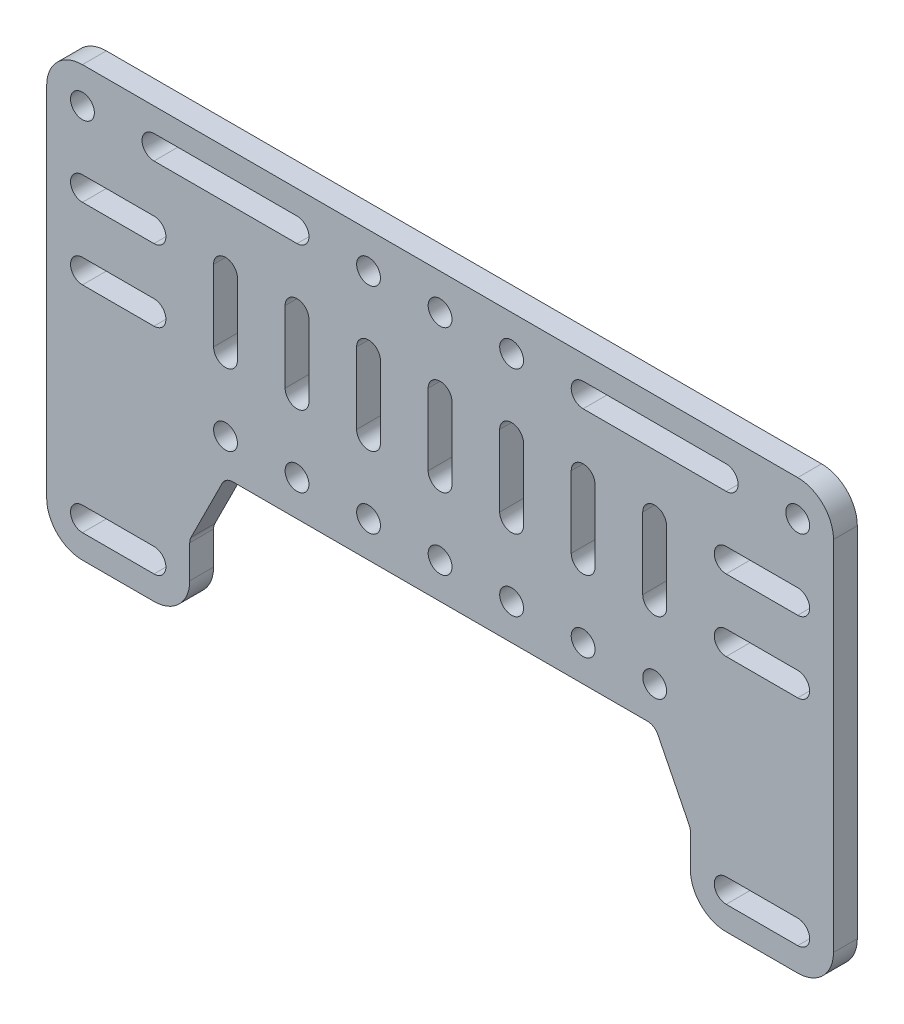
SolidWorks part; units mm, degrees
ref_plane "Alzado" through (0, 0, 0) normal (0, 0, 1) x (1, 0, 0)
ref_plane "Planta" through (0, 0, 0) normal (0, 1, 0) x (1, 0, 0)
ref_plane "Vista lateral" through (0, 0, 0) normal (1, 0, 0) x (0, 0, -1)
sketch "Model" plane through (0, 0, 0) normal (0, 0, 1) x (1, 0, 0)
  line L0 (-1388.2269, 304.4077) -> (-1478.2269, 304.4077)
  line L1 (-1383.7269, 254.9077) -> (-1383.7269, 299.9077)
  line L2 (-1397.2269, 250.4077) -> (-1388.2269, 250.4077)
  line L3 (-1482.7269, 299.9077) -> (-1482.7269, 254.9077)
  line L4 (-1478.2269, 250.4077) -> (-1469.2269, 250.4077)
  line L5 (-1464.7269, 254.9077) -> (-1464.7269, 259.0536)
  line L6 (-1401.7269, 254.9077) -> (-1401.7269, 259.0536)
  line L7 (-1459.2999, 268.4077) -> (-1407.154, 268.4077)
  line L8 (-1458.7269, 281.9077) -> (-1458.7269, 290.9077)
  line L9 (-1461.7269, 290.9077) -> (-1461.7269, 281.9077)
  line L10 (-1449.7269, 281.9077) -> (-1449.7269, 290.9077)
  line L11 (-1452.7269, 290.9077) -> (-1452.7269, 281.9077)
  line L12 (-1440.7269, 281.9077) -> (-1440.7269, 290.9077)
  line L13 (-1443.7269, 290.9077) -> (-1443.7269, 281.9077)
  line L14 (-1431.7269, 281.9077) -> (-1431.7269, 290.9077)
  line L15 (-1434.7269, 290.9077) -> (-1434.7269, 281.9077)
  line L16 (-1422.7269, 281.9077) -> (-1422.7269, 290.9077)
  line L17 (-1425.7269, 290.9077) -> (-1425.7269, 281.9077)
  line L18 (-1413.7269, 281.9077) -> (-1413.7269, 290.9077)
  line L19 (-1416.7269, 290.9077) -> (-1416.7269, 281.9077)
  line L20 (-1404.7269, 281.9077) -> (-1404.7269, 290.9077)
  line L21 (-1407.7269, 290.9077) -> (-1407.7269, 281.9077)
  line L22 (-1478.2269, 292.4077) -> (-1469.2269, 292.4077)
  line L23 (-1478.2269, 289.4077) -> (-1469.2269, 289.4077)
  line L24 (-1397.2269, 292.4077) -> (-1388.2269, 292.4077)
  line L25 (-1397.2269, 280.4077) -> (-1388.2269, 280.4077)
  line L26 (-1469.2269, 298.4077) -> (-1451.2269, 298.4077)
  line L27 (-1469.2269, 301.4077) -> (-1451.2269, 301.4077)
  line L28 (-1415.2269, 301.4077) -> (-1397.2269, 301.4077)
  line L29 (-1415.2269, 298.4077) -> (-1397.2269, 298.4077)
  line L30 (-1397.2269, 283.4077) -> (-1388.2269, 283.4077)
  line L31 (-1397.2269, 289.4077) -> (-1388.2269, 289.4077)
  line L32 (-1464.5686, 259.7244) -> (-1460.6415, 267.5785)
  line L33 (-1405.8123, 267.5785) -> (-1401.8853, 259.7244)
  line L34 (-1478.2269, 280.4077) -> (-1469.2269, 280.4077)
  line L35 (-1478.2269, 283.4077) -> (-1469.2269, 283.4077)
  line L36 (-1478.2269, 256.4077) -> (-1469.2269, 256.4077)
  line L37 (-1478.2269, 253.4077) -> (-1469.2269, 253.4077)
  line L38 (-1397.2269, 256.4077) -> (-1388.2269, 256.4077)
  line L39 (-1397.2269, 253.4077) -> (-1388.2269, 253.4077)
  arc A0 (-1388.2269, 250.4077) -> (-1383.7269, 254.9077) centre (-1388.2269, 254.9077) ccw
  arc A1 (-1482.7269, 254.9077) -> (-1478.2269, 250.4077) centre (-1478.2269, 254.9077) ccw
  arc A2 (-1383.7269, 299.9077) -> (-1388.2269, 304.4077) centre (-1388.2269, 299.9077) ccw
  arc A3 (-1478.2269, 304.4077) -> (-1482.7269, 299.9077) centre (-1478.2269, 299.9077) ccw
  circle A4 centre (-1424.2269, 299.9077) radius 1.5
  circle A5 centre (-1433.2269, 299.9077) radius 1.5
  circle A6 centre (-1442.2269, 299.9077) radius 1.5
  circle A7 centre (-1478.2269, 299.9077) radius 1.5
  circle A8 centre (-1388.2269, 299.9077) radius 1.5
  circle A9 centre (-1406.2269, 272.9077) radius 1.5
  circle A10 centre (-1415.2269, 272.9077) radius 1.5
  circle A11 centre (-1424.2269, 272.9077) radius 1.5
  circle A12 centre (-1433.2269, 272.9077) radius 1.5
  circle A13 centre (-1442.2269, 272.9077) radius 1.5
  circle A14 centre (-1451.2269, 272.9077) radius 1.5
  circle A15 centre (-1460.2269, 272.9077) radius 1.5
  arc A16 (-1469.2269, 250.4077) -> (-1464.7269, 254.9077) centre (-1469.2269, 254.9077) ccw
  arc A17 (-1401.7269, 254.9077) -> (-1397.2269, 250.4077) centre (-1397.2269, 254.9077) ccw
  arc A18 (-1461.7269, 281.9077) -> (-1458.7269, 281.9077) centre (-1460.2269, 281.9077) ccw
  arc A19 (-1458.7269, 290.9077) -> (-1461.7269, 290.9077) centre (-1460.2269, 290.9077) ccw
  arc A20 (-1452.7269, 281.9077) -> (-1449.7269, 281.9077) centre (-1451.2269, 281.9077) ccw
  arc A21 (-1449.7269, 290.9077) -> (-1452.7269, 290.9077) centre (-1451.2269, 290.9077) ccw
  arc A22 (-1443.7269, 281.9077) -> (-1440.7269, 281.9077) centre (-1442.2269, 281.9077) ccw
  arc A23 (-1440.7269, 290.9077) -> (-1443.7269, 290.9077) centre (-1442.2269, 290.9077) ccw
  arc A24 (-1434.7269, 281.9077) -> (-1431.7269, 281.9077) centre (-1433.2269, 281.9077) ccw
  arc A25 (-1431.7269, 290.9077) -> (-1434.7269, 290.9077) centre (-1433.2269, 290.9077) ccw
  arc A26 (-1425.7269, 281.9077) -> (-1422.7269, 281.9077) centre (-1424.2269, 281.9077) ccw
  arc A27 (-1422.7269, 290.9077) -> (-1425.7269, 290.9077) centre (-1424.2269, 290.9077) ccw
  arc A28 (-1416.7269, 281.9077) -> (-1413.7269, 281.9077) centre (-1415.2269, 281.9077) ccw
  arc A29 (-1413.7269, 290.9077) -> (-1416.7269, 290.9077) centre (-1415.2269, 290.9077) ccw
  arc A30 (-1407.7269, 281.9077) -> (-1404.7269, 281.9077) centre (-1406.2269, 281.9077) ccw
  arc A31 (-1404.7269, 290.9077) -> (-1407.7269, 290.9077) centre (-1406.2269, 290.9077) ccw
  arc A32 (-1451.2269, 298.4077) -> (-1451.2269, 301.4077) centre (-1451.2269, 299.9077) ccw
  arc A33 (-1415.2269, 301.4077) -> (-1415.2269, 298.4077) centre (-1415.2269, 299.9077) ccw
  arc A34 (-1478.2269, 292.4077) -> (-1478.2269, 289.4077) centre (-1478.2269, 290.9077) ccw
  arc A35 (-1469.2269, 289.4077) -> (-1469.2269, 292.4077) centre (-1469.2269, 290.9077) ccw
  arc A36 (-1397.2269, 292.4077) -> (-1397.2269, 289.4077) centre (-1397.2269, 290.9077) ccw
  arc A37 (-1388.2269, 289.4077) -> (-1388.2269, 292.4077) centre (-1388.2269, 290.9077) ccw
  arc A38 (-1397.2269, 283.4077) -> (-1397.2269, 280.4077) centre (-1397.2269, 281.9077) ccw
  arc A39 (-1388.2269, 280.4077) -> (-1388.2269, 283.4077) centre (-1388.2269, 281.9077) ccw
  arc A40 (-1459.2999, 268.4077) -> (-1460.6415, 267.5785) centre (-1459.2999, 266.9077) ccw
  arc A41 (-1405.8123, 267.5785) -> (-1407.154, 268.4077) centre (-1407.154, 266.9077) ccw
  arc A42 (-1401.7269, 259.0536) -> (-1401.8853, 259.7244) centre (-1403.2269, 259.0536) ccw
  arc A43 (-1464.5686, 259.7244) -> (-1464.7269, 259.0536) centre (-1463.2269, 259.0536) ccw
  arc A44 (-1478.2269, 283.4077) -> (-1478.2269, 280.4077) centre (-1478.2269, 281.9077) ccw
  arc A45 (-1469.2269, 280.4077) -> (-1469.2269, 283.4077) centre (-1469.2269, 281.9077) ccw
  arc A46 (-1478.2269, 256.4077) -> (-1478.2269, 253.4077) centre (-1478.2269, 254.9077) ccw
  arc A47 (-1469.2269, 253.4077) -> (-1469.2269, 256.4077) centre (-1469.2269, 254.9077) ccw
  arc A48 (-1397.2269, 256.4077) -> (-1397.2269, 253.4077) centre (-1397.2269, 254.9077) ccw
  arc A49 (-1388.2269, 253.4077) -> (-1388.2269, 256.4077) centre (-1388.2269, 254.9077) ccw
  arc A50 (-1469.2269, 301.4077) -> (-1469.2269, 298.4077) centre (-1469.2269, 299.9077) ccw
  arc A51 (-1397.2269, 298.4077) -> (-1397.2269, 301.4077) centre (-1397.2269, 299.9077) ccw
extrude "Saliente-Extruir1" add sketch "Model" along normal blind 3
